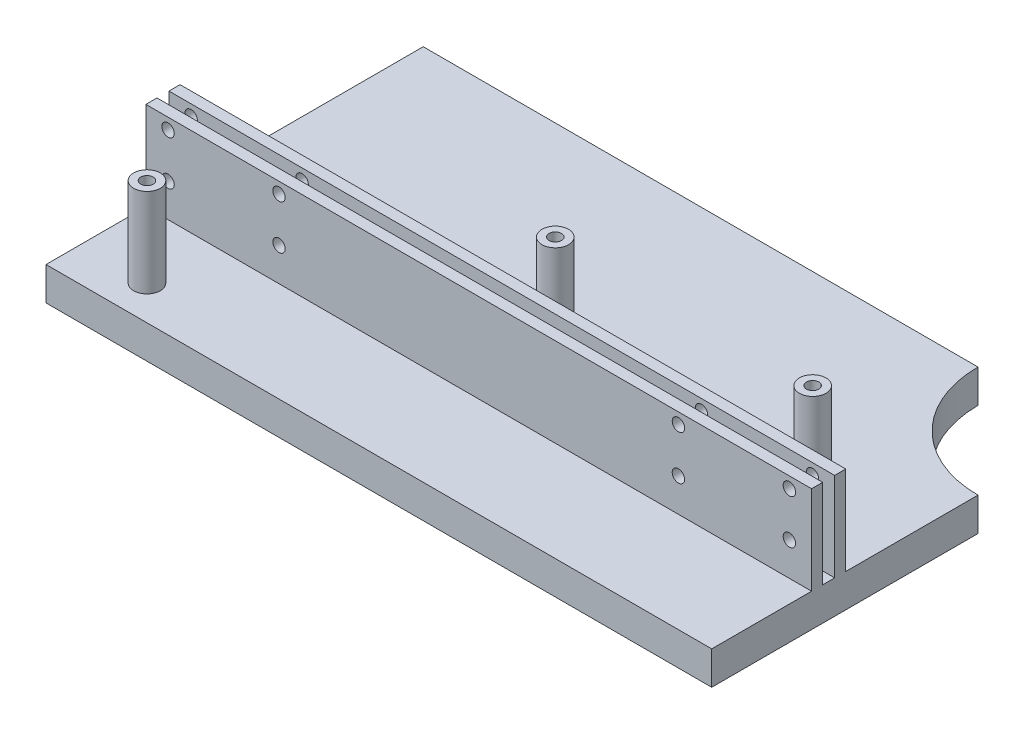
SolidWorks part; units mm, degrees
ref_plane "Front Plane" through (0, 0, 0) normal (0, 0, 1) x (1, 0, 0)
ref_plane "Top Plane" through (0, 0, 0) normal (0, 1, 0) x (1, 0, 0)
ref_plane "Right Plane" through (0, 0, 0) normal (1, 0, 0) x (0, 0, -1)
sketch "Sketch1" plane through (0, 0, 0) normal (0, 1, 0) x (1, 0, 0)
  line L1 (-150, 85) -> (-25, 85)
  line L2 (-150, 85) -> (-150, 0)
  line L3 (-150, 0) -> (0, 0)
  line L4 (0, 60) -> (0, 0)
  arc A0 (-25, 85) -> (0, 60) centre (0, 85) ccw
  dimension "D2" = 50
  dimension "D1" = 150
  dimension "D3" = 60
extrude "Boss-Extrude1" add sketch "Sketch1" along normal blind 7.5
sketch "Sketch2" plane through (0, 7.5, 0) normal (0, 1, 0) x (1, 0, 0)
  line L0 (0, 0) -> (0, 60) construction
  line L1 (0, 25) -> (-150, 25)
  line L2 (0, 25) -> (0, 22.5)
  line L3 (0, 22.5) -> (-150, 22.5)
  line L4 (-150, 25) -> (-150, 22.5)
  line L5 (-150, 85) -> (-150, 0) construction
  line L7 (-150, 27.7) -> (0, 27.7)
  line L8 (-150, 27.7) -> (-150, 30.2)
  line L9 (-150, 30.2) -> (0, 30.2)
  line L10 (0, 27.7) -> (0, 30.2)
  line L11 (-150, 0) -> (0, 0) construction
  dimension "D1" = 2.5
  dimension "D2" = 25
  dimension "D3" = 2.7
extrude "Boss-Extrude2" add sketch "Sketch2" along normal blind 20
sketch "Sketch3" plane through (0, 0, -22.5) normal (0, 0, 1) x (1, 0, 0)
  line L0 (-35, 27.5) -> (-35, 7.5) construction
  line L1 (-150, 27.5) -> (0, 27.5) construction
  line L2 (-150, 7.5) -> (0, 7.5) construction
  line L3 (0, 27.5) -> (0, 7.5) construction
  line L4 (-30, 25) -> (-5, 25) construction
  line L5 (-5, 25) -> (-5, 15) construction
  line L6 (-5, 15) -> (-30, 15) construction
  line L7 (-30, 15) -> (-30, 25) construction
  line L8 (-75, 48.4224) -> (-75, -16.3407) construction
  line L9 (-120, 15) -> (-120, 25) construction
  line L10 (-145, 15) -> (-120, 15) construction
  line L11 (-145, 25) -> (-145, 15) construction
  line L12 (-120, 25) -> (-145, 25) construction
  line L13 (-115, 27.5) -> (-115, 7.5) construction
  circle A0 centre (-30, 25) radius 1.4
  circle A1 centre (-5, 25) radius 1.4
  circle A2 centre (-30, 15) radius 1.4
  circle A3 centre (-5, 15) radius 1.4
  circle A4 centre (-145, 15) radius 1.4
  circle A5 centre (-120, 15) radius 1.4
  circle A6 centre (-145, 25) radius 1.4
  circle A7 centre (-120, 25) radius 1.4
  point P28 (-75, 27.5)
  dimension "D2" = 2.8
  dimension "D1" = 35
  dimension "D3" = 5
  dimension "D4" = 2.5
  dimension "D5" = 25
  dimension "D6" = 10
extrude "Cut-Extrude1" cut sketch "Sketch3" against normal blind 10
sketch "Sketch4" plane through (0, 7.5, 0) normal (0, 1, 0) x (1, 0, 0)
  line L2 (-78, 42.75) -> (-20, 42.75) construction
  line L3 (-20, 42.75) -> (-20, 0) construction
  line L4 (-150, 0) -> (0, 0) construction
  line L5 (0, 0) -> (0, 22.5) construction
  line L6 (-150, 22.5) -> (-150, 0) construction
  circle A0 centre (-78, 42.75) radius 3
  circle A1 centre (-20, 42.75) radius 3
  circle A2 centre (-135, 7.75) radius 3
  dimension "D1" = 6
  dimension "D2" = 58
  dimension "D3" = 42.75
  dimension "D4" = 20
  dimension "D5" = 15
  dimension "D6" = 7.75
extrude "Boss-Extrude3" add sketch "Sketch4" along normal blind 20
sketch "Sketch5" plane through (0, 27.5, 0) normal (0, 1, 0) x (1, 0, 0)
  circle A0 centre (-78, 42.75) radius 1.4
  circle A1 centre (-20, 42.75) radius 1.4
  circle A2 centre (-135, 7.75) radius 1.4
  dimension "D1" = 2.8
extrude "Cut-Extrude2" cut sketch "Sketch5" against normal blind 8
